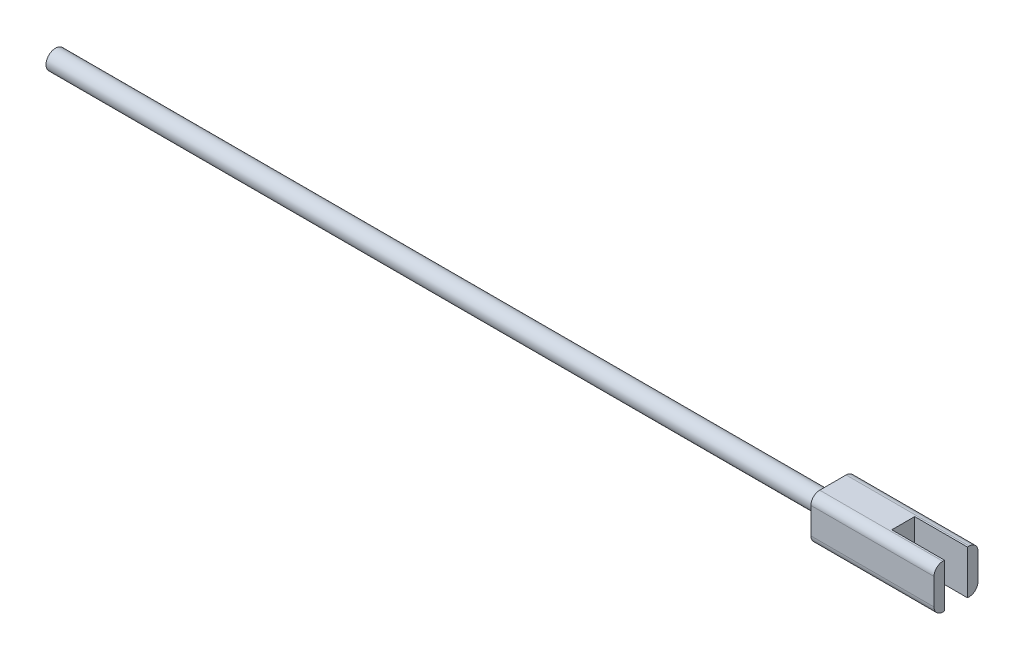
SolidWorks part; units mm, degrees
ref_plane "Front Plane" through (0, 0, 0) normal (0, 0, 1) x (1, 0, 0)
ref_plane "Top Plane" through (0, 0, 0) normal (0, 1, 0) x (1, 0, 0)
ref_plane "Right Plane" through (0, 0, 0) normal (1, 0, 0) x (0, 0, -1)
sketch "Sketch1" plane through (0, 0, 0) normal (1, 0, 0) x (0, 0, -1)
  circle A0 centre (0, 0) radius 1.09
extrude "Boss-Extrude1" add sketch "Sketch1" along normal blind 90.392
ref_plane "Plane1" through (88.392, 0, 0) normal (1, 0, 0) x (0, 0, -1)
sketch "Sketch2" plane through (88.392, 0, 0) normal (1, 0, 0) x (0, 0, -1)
  line L0 (-1.5, -2.5) -> (1.5, -2.5)
  line L1 (2.5, -1.5) -> (2.5, 1.5)
  line L2 (1.5, 2.5) -> (-1.5, 2.5)
  line L3 (-2.5, 1.5) -> (-2.5, -1.5)
  arc A0 (1.5, -2.5) -> (2.5, -1.5) centre (1.5, -1.5) ccw
  arc A1 (2.5, 1.5) -> (1.5, 2.5) centre (1.5, 1.5) ccw
  arc A2 (-1.5, 2.5) -> (-2.5, 1.5) centre (-1.5, 1.5) ccw
  arc A3 (-2.5, -1.5) -> (-1.5, -2.5) centre (-1.5, -1.5) ccw
extrude "Boss-Extrude2" add sketch "Sketch2" along normal blind 14
sketch "Sketch3" plane through (0, 0, 0) normal (0, 1, 0) x (1, 0, 0)
  line L0 (96.392, 1.3) -> (103.392, 1.3)
  line L1 (103.392, 1.3) -> (103.392, -1.3)
  line L2 (103.392, -1.3) -> (96.392, -1.3)
  line L3 (96.392, -1.3) -> (96.392, 1.3)
extrude "Cut-Extrude1" cut sketch "Sketch3" against normal through all and the other way through all
